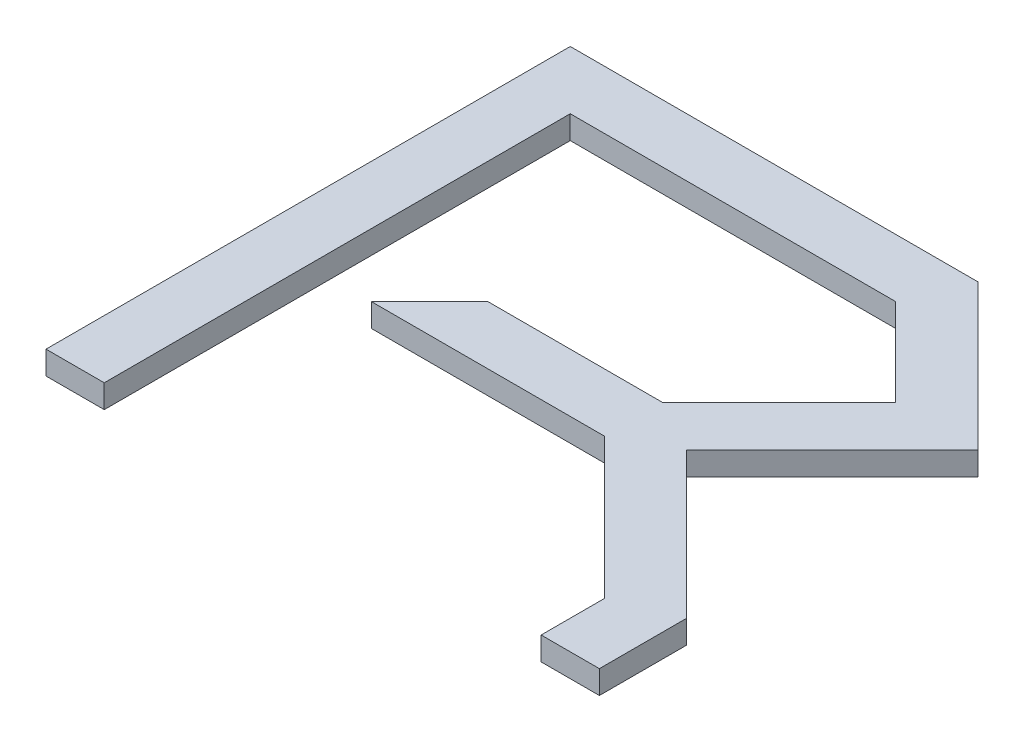
SolidWorks part; units mm, degrees
ref_plane "Front Plane" through (0, 0, 0) normal (0, 0, 1) x (1, 0, 0)
ref_plane "Top Plane" through (0, 0, 0) normal (0, 1, 0) x (1, 0, 0)
ref_plane "Right Plane" through (0, 0, 0) normal (1, 0, 0) x (0, 0, -1)
sketch "Sketch2" plane through (0, 0, 0) normal (0, 1, 0) x (1, 0, 0)
  line L0 (-12.5, 20) -> (15.4289, 20)
  line L1 (-17.5, 25) -> (17.5, 25)
  line L2 (-17.5, 25) -> (-17.5, -20)
  line L5 (15.4289, 20) -> (22.9289, 12.5)
  line L6 (22.9289, 12.5) -> (12.9289, 2.5)
  line L7 (12.9289, -2.5) -> (25, -14.5711)
  line L8 (25, -14.5711) -> (25, -20)
  line L9 (17.5, 25) -> (30, 12.5)
  line L10 (30, 12.5) -> (17.5, 0)
  line L11 (30, -12.5) -> (30, -20) construction
  line L12 (17.5, 0) -> (30, -12.5)
  line L13 (30, -12.5) -> (30, -20)
  line L17 (-12.5, 20) -> (-12.5, -20)
  line L20 (12.9289, 2.5) -> (-2.0711, 2.5)
  line L21 (12.9289, -2.5) -> (-7.0711, -2.5)
  line L22 (-7.0711, -2.5) -> (-2.0711, 2.5)
  line L23 (22.9289, 12.5) -> (10.4289, 0) construction
  line L24 (10.4289, 0) -> (25, -14.5711) construction
  line L25 (-12.5, -20) -> (-17.5, -20)
  line L26 (25, -20) -> (30, -20)
  line L27 (-17.5, 25) -> (-17.5, -25) construction
  line L28 (-17.5, -25) -> (17.5, -25) construction
  line L29 (30, -25) -> (17.5, -25) construction
  line L30 (30, -12.5) -> (30, -25) construction
  line L31 (-12.5, -20) -> (17.5, -20) construction
  line L32 (25, -20) -> (17.5, -20) construction
  point P0 (0, 0)
  point P19 (0, 0)
  dimension "D3" = 5
extrude "Boss-Extrude1" add sketch "Sketch2" along normal blind 2
